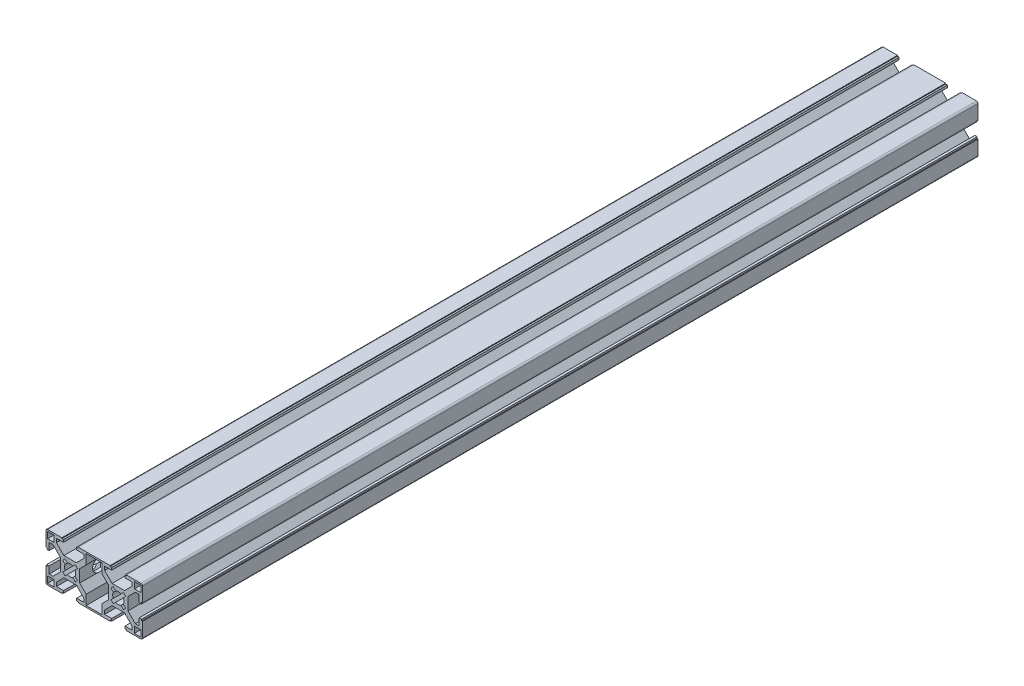
SolidWorks part; units mm, degrees
material "6063-T83"
ref_plane "Plano frontal" through (0, 0, 0) normal (0, 0, 1) x (1, 0, 0)
ref_plane "Plano superior" through (0, 0, 0) normal (0, 1, 0) x (1, 0, 0)
ref_plane "Plano direito" through (0, 0, 0) normal (1, 0, 0) x (0, 0, -1)
sketch "Esboço1" plane through (0, 0, 0) normal (0, 0, 1) x (1, 0, 0)
  line L5 (0, 0) -> (-17.7944, 17.7944) construction
  line L6 (0, 3.5) -> (0, 6)
  line L8 (0, 6) -> (-3.8787, 6)
  line L9 (-3.5, 0) -> (-6, 0)
  line L48 (-6, 0) -> (-6, 3.8787)
  line L49 (-3.8787, 6) -> (-8.5, 10.6213)
  line L50 (-6, 3.8787) -> (-10.6213, 8.5)
  line L51 (0, 0) -> (-12.921, 0) construction
  line L52 (-8.5, 13) -> (-4.1, 13)
  line L53 (-4.1, 13) -> (-4.1, 14.5)
  line L54 (-4.1, 14.5) -> (-5.1, 14.5)
  line L55 (-5.1, 14.5) -> (-5.1, 15)
  line L56 (-5.1, 15) -> (-15, 15)
  line L57 (-15, 5.1) -> (-15, 15)
  line L58 (-14.5, 5.1) -> (-15, 5.1)
  line L59 (-14.5, 4.1) -> (-14.5, 5.1)
  line L60 (-13, 4.1) -> (-14.5, 4.1)
  line L61 (-13, 8.5) -> (-13, 4.1)
  line L62 (-1.6646, 3.0788) -> (-3.182, 4.5962)
  line L63 (-3.0788, 1.6646) -> (-4.5962, 3.182)
  line L64 (-4.5962, 3.182) -> (-3.182, 4.5962)
  line L65 (-8.5, 13) -> (-8.5, 10.6213)
  line L66 (-10, 14) -> (-14, 14)
  line L67 (-10, 14) -> (-10, 10)
  line L68 (-10, 10) -> (-14, 10)
  line L69 (-14, 14) -> (-14, 10)
  line L70 (-10, 14) -> (-14, 10) construction
  line L71 (-10, 10) -> (-14, 14) construction
  line L72 (-13, 8.5) -> (-10.6213, 8.5)
  circle A1 centre (0, 0) radius 3.5
  point P25 (-12, 12)
  dimension "D5" = 10.9
  dimension "D9" = 5.5
  dimension "D10" = 2
  dimension "D11" = 4
  dimension "D12" = 4
  dimension "D13" = 1
  dimension "D1" = 7
  dimension "D2" = 6
  dimension "D3" = 3
  dimension "D4" = 9.9
  dimension "D6" = 0.5
  dimension "D7" = 1.5
  dimension "D8" = 15
  dimension "D14" = 6.5
extrude "Ressalto-extrusão1" add sketch "Esboço1" along normal blind 520 contours A1 L6 L8 L49 L65 L52 L53 L54 L55 L56 L57 L58 L59 L60 L61 L72 L50 L48 L9 L63 L64 L62 L69 L66 L67 L68
sketch "Esboço3" plane through (0, 0, 0) normal (1, 0, 0) x (0, 0, -1)
  line L0 (0, 0) -> (-1000, 0) construction
  dimension "D1" = 1000
pattern_circular "PadrãoCircular1" count 4 every 90 about axis through (0, 0, 0) along (0, 0, 1) of "Ressalto-extrusão1"
pattern_linear "Padrão linear1" count 2 spacing 30 along (1, 0, 0) of "Ressalto-extrusão1", "PadrãoCircular1"
sketch "Esboço4" plane through (0, 0, 0) normal (0, 0, -1) x (-1, 0, 0)
  line L0 (-20, 14) -> (-20, -14)
  line L1 (-20, -14) -> (-10, -14)
  line L2 (-10, -14) -> (-10, 14)
  line L3 (-10, 14) -> (-20, 14)
extrude "Corte-extrusão1" cut sketch "Esboço4" against normal through all
fillet "Filete1" radius 1 4 edges at (45, -15, 260) (45, 15, 260) (-15, 15, 260) (-15, -15, 260)
sketch "Sketch1" plane through (-6, 0, 0) normal (-1, 0, 0) x (0, 0, 1)
  circle A0 centre (12, 0) radius 4
  dimension "D1" = 8
  dimension "D2" = 12
extrude "Cut-Extrude1" cut sketch "Sketch1" against normal through all both and the other way through all
ref_plane "Plane1" through (0, 0, 260) normal (0, 0, 1) x (1, 0, 0)
mirror "Mirror1" about plane through (0, 0, 260) normal (0, 0, 1) of "Cut-Extrude1"
sketch "Sketch2" plane through (-15, 0, 0) normal (-1, 0, 0) x (0, 0, 1)
  circle A0 centre (12, 0) radius 4
  circle A1 centre (508, 0) radius 4
  dimension "D1" = 8
  dimension "D2" = 8
ref_plane "Plane2" through (0, 0, 0) normal (0, -1, 0) x (-1, 0, 0)
ref_plane "Plane3" through (15, 0, 0) normal (-1, 0, 0) x (0, 0, 1)
sketch "Sketch4" plane through (45, 0, 0) normal (1, 0, 0) x (0, 0, -1)
  circle A0 centre (-12, 0) radius 10.7346
  circle A1 centre (-508, 0) radius 8.2077
